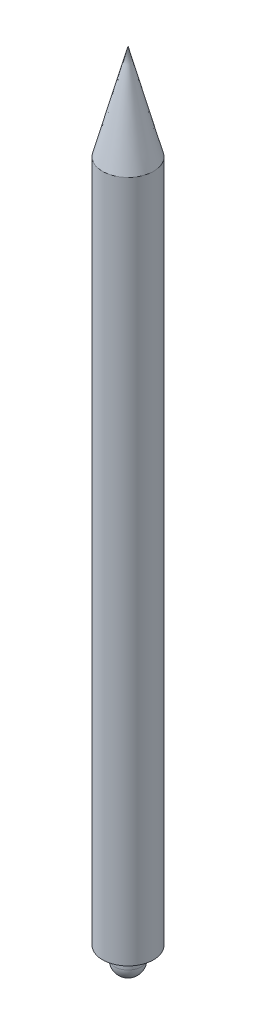
SolidWorks part; units mm, degrees
ref_plane "Front Plane" through (0, 0, 0) normal (0, 0, 1) x (1, 0, 0)
ref_plane "Top Plane" through (0, 0, 0) normal (0, 1, 0) x (1, 0, 0)
ref_plane "Right Plane" through (0, 0, 0) normal (1, 0, 0) x (0, 0, -1)
sketch "Sketch1" plane through (0, 0, 0) normal (0, 1, 0) x (1, 0, 0)
  circle A0 centre (0, 0) radius 4.25
  dimension "D1" = 8.5
extrude "Boss-Extrude1" add sketch "Sketch1" along normal blind 114
sketch "Sketch2" plane through (0, 0, 0) normal (0, 0, 1) x (1, 0, 0)
  line L0 (2.25, 0) -> (2.25, -2)
  line L1 (0, 0) -> (0, -4.25)
  line L2 (2.25, 0) -> (0, 0)
  arc A0 (0, -4.25) -> (2.25, -2) centre (0, -2) ccw
  dimension "D1" = 2
  dimension "D2" = 2
  dimension "D3" = 4.25
  dimension "D4" = 2
  dimension "D5" = 2.25
revolve "Revolve1" add sketch "Sketch2" angle 360 about L1
sketch "Sketch3" plane through (0, 0, 0) normal (0, 0, 1) x (1, 0, 0)
  line L0 (0, 114) -> (0, 130)
  line L1 (0, 130) -> (4.25, 114)
  line L2 (4.25, 114) -> (0, 114)
  point P4 (4.25, 114)
  dimension "D1" = 16
  dimension "D2" = 4.25
revolve "Revolve2" add sketch "Sketch3" angle 360 about L0
